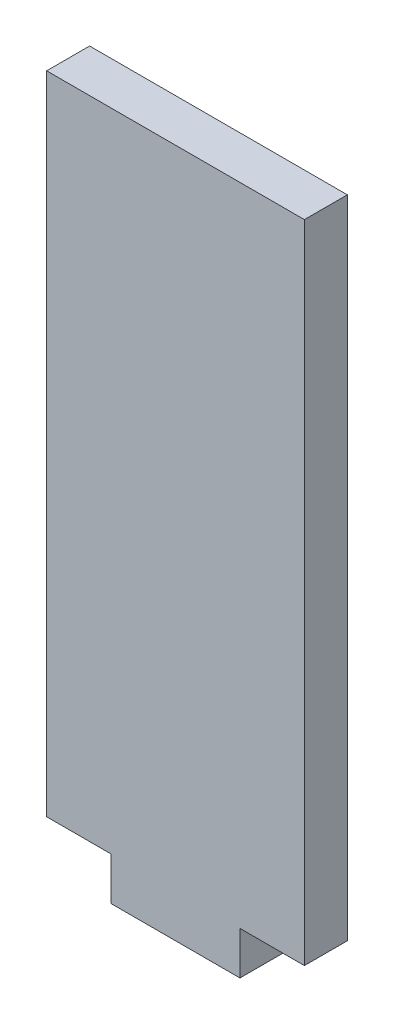
SolidWorks part; units mm, degrees
ref_plane "前视基准面" through (0, 0, 0) normal (0, 0, 1) x (1, 0, 0)
ref_plane "上视基准面" through (0, 0, 0) normal (0, 1, 0) x (1, 0, 0)
ref_plane "右视基准面" through (0, 0, 0) normal (1, 0, 0) x (0, 0, -1)
sketch "草图1" plane through (0, 0, 0) normal (0, 0, 1) x (1, 0, 0)
  line L0 (-6, 0) -> (-6, 15)
  line L1 (-6, 0) -> (-3, 0)
  line L3 (6, 0) -> (6, 15)
  line L4 (-3, 0) -> (-3, -2)
  line L6 (-3, -2) -> (3, -2)
  line L7 (3, 0) -> (3, -2)
  line L8 (-6, 15) -> (-6, 30.0788)
  line L9 (-6, 30.0788) -> (6, 30.0788)
  line L10 (6, 30.0788) -> (6, 15)
  line L11 (3, 0) -> (6, 0)
extrude "凸台-拉伸1" add sketch "草图1" along normal blind 2 contours L9 L10 L3 L11 L7 L6 L4 L1 L0 L8
sketch3d "3D草图1"
  spline S0 degree 3 poles (-3.7273, 8.6553, 2) (-3.7067, 8.1296, 2) (-3.6711, 7.872, 2) (-3.5513, 7.3672, 2) (-3.4659, 7.1174, 2) (-3.2494, 6.6421, 2) (-3.1195, 6.4176, 2) (-2.8165, 5.9948, 2) (-2.6417, 5.7953, 2) (-2.2624, 5.44, 2) (-2.0567, 5.2819, 2) (-1.6127, 5.0056, 2) (-1.3762, 4.8894, 2) (-0.8905, 4.7074, 2) (-0.6379, 4.64, 2) (-0.1196, 4.5564, 2) (0.1397, 4.5409, 2) (0.6585, 4.5609, 2) (0.921, 4.5974, 2) (1.4274, 4.7202, 2) (1.6722, 4.806, 2) (2.1451, 5.0262, 2) (2.3726, 5.1613, 2) (2.7908, 5.4689, 2) (2.9843, 5.6425, 2) (3.3389, 6.0308, 2) (3.4946, 6.2396, 2) (3.7633, 6.6836, 2) (3.8775, 6.9217, 2) (4.0561, 7.4125, 2) (4.1207, 7.6637, 2) (4.2013, 8.1778, 2) (4.2167, 8.4425, 2) (4.1964, 8.9618, 2) (4.1616, 9.219, 2) (4.0412, 9.7281, 2) (3.9559, 9.9771, 2) (3.7413, 10.4493, 2) (3.6109, 10.6756, 2) (3.3051, 11.1025, 2) (3.1338, 11.2978, 2) (2.7555, 11.653, 2) (2.5457, 11.8144, 2) (2.1029, 12.0899, 2) (1.8704, 12.2046, 2) (1.3828, 12.3879, 2) (1.1266, 12.456, 2) (0.614, 12.539, 2) (0.3548, 12.5551, 2) (-0.1694, 12.5352, 2) (-0.4288, 12.499, 2) (-0.9331, 12.3772, 2) (-1.1818, 12.2904, 2) (-1.656, 12.0696, 2) (-1.8793, 11.9372, 2) (-2.2986, 11.6295, 2) (-2.4959, 11.4523, 2) (-2.8467, 11.0683, 2) (-3.0023, 10.8606, 2) (-3.2735, 10.4133, 2) (-3.3872, 10.1758, 2) (-3.5651, 9.6884, 2) (-3.6307, 9.4355, 2) (-3.7121, 8.9165, 2) (-3.7273, 8.6553, 2) (-3.7067, 8.1296, 2) (-3.6711, 7.872, 2) knots -0.03125 -0.03125 0 0 0.03125 0.03125 0.0625 0.0625 0.09375 0.09375 0.125 0.125 0.15625 0.15625 0.1875 0.1875 0.21875 0.21875 0.25 0.25 0.28125 0.28125 0.3125 0.3125 0.34375 0.34375 0.375 0.375 0.40625 0.40625 0.4375 0.4375 0.46875 0.46875 0.5 0.5 0.53125 0.53125 0.5625 0.5625 0.59375 0.59375 0.625 0.625 0.65625 0.65625 0.6875 0.6875 0.71875 0.71875 0.75 0.75 0.78125 0.78125 0.8125 0.8125 0.84375 0.84375 0.875 0.875 0.90625 0.90625 0.9375 0.9375 0.96875 0.96875 1 1 1.03125 1.03125 1.0625 only from (-3.717, 8.3924, 2) to (-3.717, 8.3924, 2)
  spline S1 degree 3 poles (-3.7273, 8.6553, 2) (-3.7067, 8.1296, 2) (-3.6711, 7.872, 2) (-3.5513, 7.3672, 2) (-3.4659, 7.1174, 2) (-3.2494, 6.6421, 2) (-3.1195, 6.4176, 2) (-2.8165, 5.9948, 2) (-2.6417, 5.7953, 2) (-2.2624, 5.44, 2) (-2.0567, 5.2819, 2) (-1.6127, 5.0056, 2) (-1.3762, 4.8894, 2) (-0.8905, 4.7074, 2) (-0.6379, 4.64, 2) (-0.1196, 4.5564, 2) (0.1397, 4.5409, 2) (0.6585, 4.5609, 2) (0.921, 4.5974, 2) (1.4274, 4.7202, 2) (1.6722, 4.806, 2) (2.1451, 5.0262, 2) (2.3726, 5.1613, 2) (2.7908, 5.4689, 2) (2.9843, 5.6425, 2) (3.3389, 6.0308, 2) (3.4946, 6.2396, 2) (3.7633, 6.6836, 2) (3.8775, 6.9217, 2) (4.0561, 7.4125, 2) (4.1207, 7.6637, 2) (4.2013, 8.1778, 2) (4.2167, 8.4425, 2) (4.1964, 8.9618, 2) (4.1616, 9.219, 2) (4.0412, 9.7281, 2) (3.9559, 9.9771, 2) (3.7413, 10.4493, 2) (3.6109, 10.6756, 2) (3.3051, 11.1025, 2) (3.1338, 11.2978, 2) (2.7555, 11.653, 2) (2.5457, 11.8144, 2) (2.1029, 12.0899, 2) (1.8704, 12.2046, 2) (1.3828, 12.3879, 2) (1.1266, 12.456, 2) (0.614, 12.539, 2) (0.3548, 12.5551, 2) (-0.1694, 12.5352, 2) (-0.4288, 12.499, 2) (-0.9331, 12.3772, 2) (-1.1818, 12.2904, 2) (-1.656, 12.0696, 2) (-1.8793, 11.9372, 2) (-2.2986, 11.6295, 2) (-2.4959, 11.4523, 2) (-2.8467, 11.0683, 2) (-3.0023, 10.8606, 2) (-3.2735, 10.4133, 2) (-3.3872, 10.1758, 2) (-3.5651, 9.6884, 2) (-3.6307, 9.4355, 2) (-3.7121, 8.9165, 2) (-3.7273, 8.6553, 2) (-3.7067, 8.1296, 2) (-3.6711, 7.872, 2) knots -0.03125 -0.03125 0 0 0.03125 0.03125 0.0625 0.0625 0.09375 0.09375 0.125 0.125 0.15625 0.15625 0.1875 0.1875 0.21875 0.21875 0.25 0.25 0.28125 0.28125 0.3125 0.3125 0.34375 0.34375 0.375 0.375 0.40625 0.40625 0.4375 0.4375 0.46875 0.46875 0.5 0.5 0.53125 0.53125 0.5625 0.5625 0.59375 0.59375 0.625 0.625 0.65625 0.65625 0.6875 0.6875 0.71875 0.71875 0.75 0.75 0.78125 0.78125 0.8125 0.8125 0.84375 0.84375 0.875 0.875 0.90625 0.90625 0.9375 0.9375 0.96875 0.96875 1 1 1.03125 1.03125 1.0625 only from (-3.717, 8.3924, 2) to (-3.717, 8.3924, 2)
